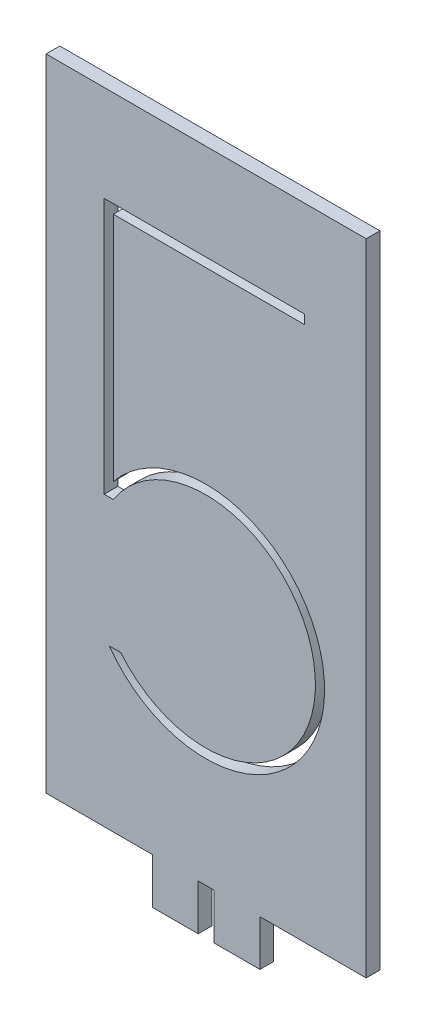
SolidWorks part; units mm, degrees
material "Glas"
ref_plane "Ebene vorne" through (0, 0, 0) normal (0, 0, 1) x (1, 0, 0)
ref_plane "Ebene oben" through (0, 0, 0) normal (0, 1, 0) x (1, 0, 0)
ref_plane "Ebene rechts" through (0, 0, 0) normal (1, 0, 0) x (0, 0, -1)
sketch "Skizze1" plane through (0, 0, 0) normal (0, 0, 1) x (1, 0, 0)
  line L1 (0, 0) -> (35, 0)
  line L2 (0, 0) -> (0, 75)
  line L3 (0, 75) -> (35, 75)
  line L4 (35, 0) -> (35, 75)
  dimension "D1" = 35
  dimension "D2" = 75
extrude "Aufsatz-Linear austragen1" add sketch "Skizze1" along normal blind 1.5
sketch "Skizze2" plane through (0, 0, 1.5) normal (0, 0, 1) x (1, 0, 0)
  line L0 (0, 0) -> (35, 0) construction
  line L1 (0, 0) -> (11.63, 0)
  line L2 (0, 0) -> (0, 5)
  line L3 (0, 5) -> (11.63, 5)
  line L4 (11.63, 0) -> (11.63, 5)
  line L5 (23.38, 5) -> (35, 5)
  line L6 (23.38, 5) -> (23.38, 0)
  line L7 (23.38, 0) -> (35, 0)
  line L8 (35, 5) -> (35, 0)
  line L9 (16.63, 0) -> (18.38, 0)
  line L10 (16.63, 0) -> (16.63, 5)
  line L11 (16.63, 5) -> (18.38, 5)
  line L12 (18.38, 0) -> (18.38, 5)
  dimension "D1" = 5
  dimension "D2" = 5
  dimension "D3" = 5
  dimension "D4" = 11.63
  dimension "D5" = 1.75
  dimension "D6" = 5
extrude "Schnitt-Linear austragen1" cut sketch "Skizze2" against normal blind 1.5
sketch "Skizze10" plane through (0, 0, 1.5) normal (0, 0, 1) x (1, 0, 0)
  line L0 (7.3504, 36.4827) -> (6.3504, 36.7697)
  line L9 (8.1633, 22.3986) -> (6.9026, 22.3986)
  line L10 (35, 5) -> (23.38, 5) construction
  arc A0 (6.9026, 22.3986) -> (6.3504, 36.7697) centre (17.4487, 30) ccw
  arc A1 (8.1633, 22.3986) -> (7.3504, 36.4827) centre (17.4487, 30) ccw
  dimension "D1" = 13
  dimension "D2" = 12
  dimension "D3" = 1
  dimension "D4" = 1.2606
  dimension "D5" = 25
extrude "Schnitt-Linear austragen5" cut sketch "Skizze10" against normal blind 20
sketch "Skizze11" plane through (0, 0, 1.5) normal (0, 0, 1) x (1, 0, 0)
  line L0 (35, 75) -> (0, 75) construction
  line L1 (7.3504, 36.4827) -> (6.3504, 36.4827)
  line L3 (7.3504, 64.5) -> (6.3504, 64.5)
  line L4 (6.3504, 36.4827) -> (6.3504, 64.5)
  line L6 (7.3504, 64.5) -> (28.25, 64.5)
  line L8 (7.3504, 63.5) -> (28.25, 63.5)
  line L9 (28.25, 64.5) -> (28.25, 63.5)
  line L10 (35, 5) -> (35, 75) construction
  line L11 (7.3504, 36.4827) -> (7.3504, 63.5)
  dimension "D1" = 10.5
  dimension "D2" = 0
  dimension "D3" = 1
  dimension "D4" = 6.75
  dimension "D5" = 28.0173
extrude "Schnitt-Linear austragen6" cut sketch "Skizze11" against normal blind 20
